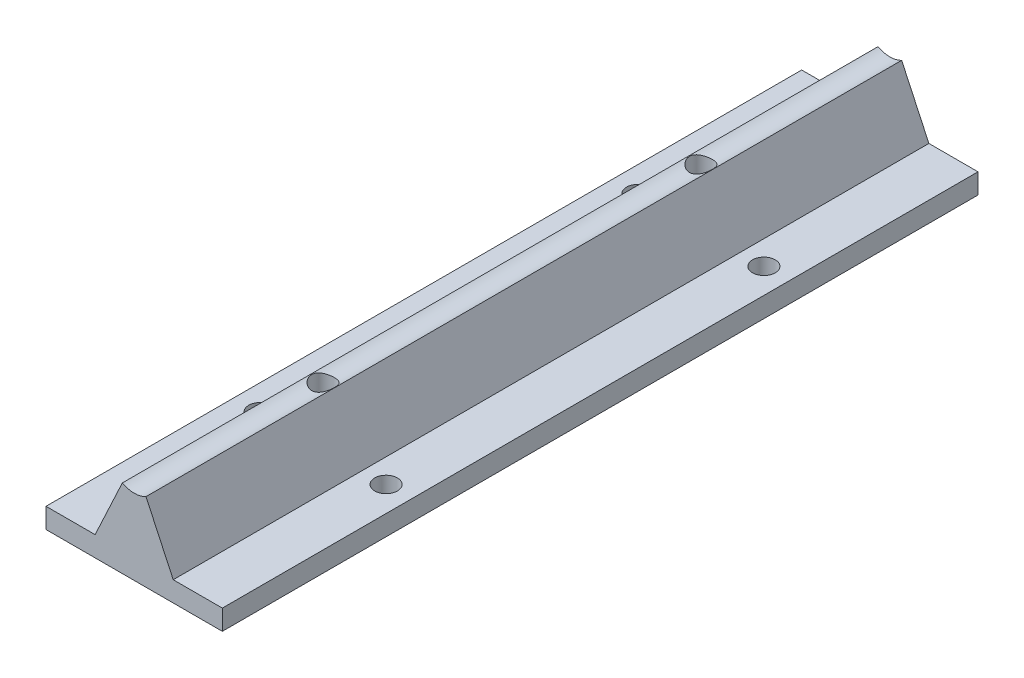
SolidWorks part; units mm, degrees
ref_plane "前视基准面" through (0, 0, 0) normal (0, 0, 1) x (1, 0, 0)
ref_plane "上视基准面" through (0, 0, 0) normal (0, 1, 0) x (1, 0, 0)
ref_plane "右视基准面" through (0, 0, 0) normal (1, 0, 0) x (0, 0, -1)
sketch "草图1" plane through (0, 0, 0) normal (0, 0, 1) x (1, 0, 0)
  line L0 (-2.35, 0) -> (2.35, 0) construction
  line L1 (0, 0) -> (0, -20) construction
  line L2 (-2.35, -4.4133) -> (-7.753, -16)
  line L3 (-7.753, -16) -> (-17.5, -16)
  line L4 (-17.5, -16) -> (-17.5, -20)
  line L5 (-17.5, -20) -> (0, -20)
  line L6 (-12.5, -20) -> (-12.5, -16) construction
  line L7 (2.35, -4.4133) -> (7.753, -16)
  line L8 (-2.25, -4.4651) -> (-2.25, -16) construction
  line L9 (7.753, -16) -> (82.753, -16) construction
  line L10 (0, -20) -> (150, -20) construction
  arc A0 (-2.35, -4.4133) -> (2.35, -4.4133) centre (0, 0) ccw
  point P5 (-12.5, -12)
  point P12 (-14.75, -20)
  dimension "(d)" = 10
  dimension "M" = 4.7
  dimension "A" = 35
  dimension "H" = 20
  dimension "H1" = 4
  dimension "J1" = 25
  dimension "N" = 4.5
  dimension "β" = 50
  dimension "N1" = 4.5
  dimension "H2" = 8
  dimension "J" = 75
  dimension "L" = 150
sketch "草图2" plane through (0, 0, 0) normal (0, 0, 1) x (1, 0, 0)
  line L0 (2.35, -4.4133) -> (7.753, -16) construction
  line L1 (-2.35, -4.4133) -> (-7.753, -16) construction
  line L2 (-7.753, -16) -> (-17.5, -16) construction
  line L3 (-17.5, -16) -> (-17.5, -20) construction
  line L4 (-17.5, -20) -> (0, -20) construction
  line L5 (0, 0) -> (0, -20) construction
  line L6 (2.35, -4.4133) -> (7.753, -16)
  line L7 (-2.35, -4.4133) -> (-7.753, -16)
  line L8 (-7.753, -16) -> (-17.5, -16)
  line L9 (-17.5, -16) -> (-17.5, -20)
  line L10 (-17.5, -20) -> (17.5, -20)
  line L11 (0, 0) -> (0, -20) construction
  line L12 (17.5, -16) -> (17.5, -20)
  line L13 (7.753, -16) -> (17.5, -16)
  arc A0 (-2.35, -4.4133) -> (2.35, -4.4133) centre (0, 0) ccw construction
  arc A1 (-2.35, -4.4133) -> (2.35, -4.4133) centre (0, 0) ccw
extrude "凸台-拉伸1" add sketch "草图2" against normal blind 150
sketch "草图3" plane through (0, 0, 0) normal (0, 1, 0) x (1, 0, 0)
  line L0 (0, 0) -> (0, 150) construction
  line L1 (2.35, 150) -> (-2.35, 150) construction
  line L2 (-14.75, 37.5) -> (-14.75, 0) construction
  circle A1 centre (12.5, 37.5) radius 2.25
  circle A2 centre (-12.5, 37.5) radius 2.25
  dimension "D1" = 37.5
extrude "切除-拉伸1" cut sketch "草图3" against normal up to vertex (20 mm away) up to point (-17.5, -20, 0)
ref_plane "基准面1" through (0, 0, -37.5) normal (0, 0, 1) x (1, 0, 0)
sketch "草图4" plane through (0, 0, -37.5) normal (0, 0, 1) x (1, 0, 0)
  line L0 (-2.25, -4.4651) -> (-2.25, -13.8151)
  line L1 (-2.25, -4.4651) -> (-2.25, -16) construction
  line L2 (-2.25, -13.8151) -> (-3.15, -13.8151)
  line L3 (-3.15, -13.8151) -> (-3.15, -20)
  line L4 (-17.5, -20) -> (0, -20) construction
  line L5 (-3.15, -20) -> (0, -20)
  line L6 (0, -20) -> (0, -4.4651)
  line L7 (0, 0) -> (0, -20) construction
  line L8 (0, -4.4651) -> (-2.25, -4.4651)
  dimension "D1" = 3.15
  dimension "D2" = 9.35
revolve "切除-旋转1" cut sketch "草图4" angle 360 about L6
pattern_linear "阵列(线性)1" count 2 spacing 75 along (0, 0, -1) of "切除-拉伸1", "切除-旋转1"
